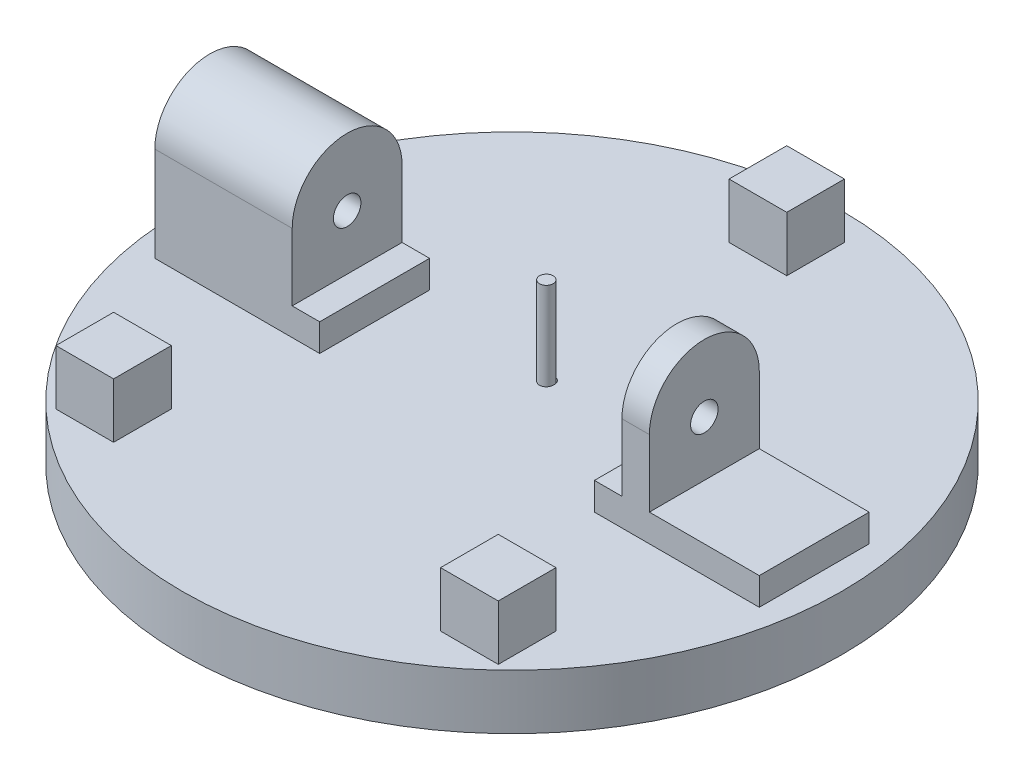
SolidWorks part; units mm, degrees
ref_plane "Front Plane" through (0, 0, 0) normal (0, 0, 1) x (1, 0, 0)
ref_plane "Top Plane" through (0, 0, 0) normal (0, 1, 0) x (1, 0, 0)
ref_plane "Right Plane" through (0, 0, 0) normal (1, 0, 0) x (0, 0, -1)
sketch "Sketch1" plane through (0, 0, 0) normal (0, 1, 0) x (1, 0, 0)
  circle A0 centre (0, 0) radius 120
  dimension "D1" = 240
extrude "Boss-Extrude1" add sketch "Sketch1" along normal mid plane 20
ref_plane "Plane1" through (-60, 0, 0) normal (1, 0, 0) x (0, 0, -1)
sketch "Sketch2" plane through (0, 10, 0) normal (0, 1, 0) x (1, 0, 0)
  line L0 (-80, 0) -> (80, 0)
  line L10 (-50, 0) -> (50, 0)
  line L11 (-50, -20) -> (-50, 20)
  line L12 (-50, 20) -> (-110, 20)
  line L13 (-50, -20) -> (-110, -20)
  line L14 (-110, -20) -> (-110, 20)
  line L15 (0, -11) -> (0, 11) construction
  line L16 (50, -20) -> (50, 20)
  line L17 (50, 20) -> (110, 20)
  line L18 (50, -20) -> (110, -20)
  line L19 (110, -20) -> (110, 20)
  point P4 (0, 0)
  point P8 (-80, 0)
  point P9 (-50, 0)
  point P20 (0, 0)
  dimension "D1" = 160
  dimension "D2" = 40
  dimension "D3" = 60
  dimension "D4" = 100
extrude "Boss-Extrude2" add sketch "Sketch2" along normal blind 10
sketch "Sketch3" plane through (0, 10, 0) normal (0, 1, 0) x (1, 0, 0)
  circle A0 centre (0, 0) radius 2.5
  circle A1 centre (0, 13) radius 2.5
  dimension "D1" = 5
  dimension "D2" = 5
  dimension "D3" = 13
extrude "Cut-Extrude1" cut sketch "Sketch3" against normal through all both and the other way through all contours A1
sketch "Sketch4" plane through (-60, 0, 0) normal (1, 0, 0) x (0, 0, -1)
  line L0 (0, 35) -> (0, 40)
  line L1 (-20, 20) -> (20, 20)
  line L2 (-20, 20) -> (-20, 44.4351)
  line L3 (-20, 20) -> (20, 20) construction
  line L4 (20, 20) -> (20, 44.4351)
  circle A0 centre (0, 40) radius 5
  arc A2 (-20, 44.4351) -> (20, 44.4351) centre (0, 44.4351) cw
  dimension "D1" = 10
  dimension "D3" = 20
  dimension "D2" = 20
  dimension "D4" = 40
extrude "Boss-Extrude4" add sketch "Sketch4" against normal blind 10 contours A2 L2 L1 L4 A0
sketch "Sketch5" plane through (-70, 0, 0) normal (-1, 0, 0) x (0, 0, 1)
  line L0 (-20, 20) -> (20, 20)
  line L1 (20, 20) -> (20, 44.4351)
  line L2 (-20, 20) -> (-20, 44.4351)
  circle A0 centre (0, 40) radius 15
  arc A1 (-20, 44.4351) -> (20, 44.4351) centre (0, 44.4351) cw
  dimension "D1" = 30
extrude "Boss-Extrude5" add sketch "Sketch5" along normal blind 40
mirror "Mirror2" about plane through (0, 0, 0) normal (1, 0, 0) of "Boss-Extrude4"
sketch "Sketch7" plane through (0, 10, 0) normal (0, 1, 0) x (1, 0, 0)
  line L0 (0, -16.5) -> (0, 16.5) construction
  circle A0 centre (0, 100) radius 10
  circle A1 centre (-70, -75) radius 10
  circle A2 centre (0, 0) radius 120 construction
  circle A3 centre (70, -75) radius 10
  point P7 (-120, 0)
  dimension "D1" = 20
  dimension "D3" = 20
  dimension "D2" = 100
  dimension "D4" = 75
  dimension "D5" = 50
  dimension "D6" = 175
  dimension "D7" = 70
extrude "Cut-Extrude2" cut sketch "Sketch7" against normal through all both and the other way through all
sketch "Sketch8" plane through (0, 10, 0) normal (0, 1, 0) x (1, 0, 0)
  line L1 (-80.5, -85.5) -> (-59.5, -85.5)
  line L2 (-80.5, -85.5) -> (-80.5, -64.5)
  line L3 (-80.5, -64.5) -> (-59.5, -64.5)
  line L4 (-59.5, -85.5) -> (-59.5, -64.5)
  line L5 (-80.5, -85.5) -> (-59.5, -64.5) construction
  line L6 (-80.5, -64.5) -> (-59.5, -85.5) construction
  line L7 (-10.5, 110.5) -> (10.5, 110.5)
  line L8 (-10.5, 110.5) -> (-10.5, 89.5)
  line L9 (-10.5, 89.5) -> (10.5, 89.5)
  line L10 (10.5, 110.5) -> (10.5, 89.5)
  line L11 (-10.5, 110.5) -> (10.5, 89.5) construction
  line L12 (-10.5, 89.5) -> (10.5, 110.5) construction
  line L13 (59.5, -85.5) -> (80.5, -85.5)
  line L14 (59.5, -85.5) -> (59.5, -64.5)
  line L15 (59.5, -64.5) -> (80.5, -64.5)
  line L16 (80.5, -85.5) -> (80.5, -64.5)
  line L17 (59.5, -85.5) -> (80.5, -64.5) construction
  line L18 (59.5, -64.5) -> (80.5, -85.5) construction
  point P0 (-70, -75)
  point P6 (0, 100)
  point P12 (70, -75)
  dimension "D1" = 21
  dimension "D2" = 21
  dimension "D3" = 21
  dimension "D4" = 21
  dimension "D5" = 21
  dimension "D6" = 21
extrude "Boss-Extrude8" add sketch "Sketch8" along normal blind 20
sketch "Sketch9" plane through (0, 0, 0) normal (0, 1, 0) x (1, 0, 0)
  line L0 (15, 12.5) -> (-15, 12.5) construction
  circle A0 centre (0, 12.5) radius 2.5
  dimension "D1" = 5
extrude "Boss-Extrude9" add sketch "Sketch9" along normal blind 42 and the other way up to surface (35.0767 mm away)
